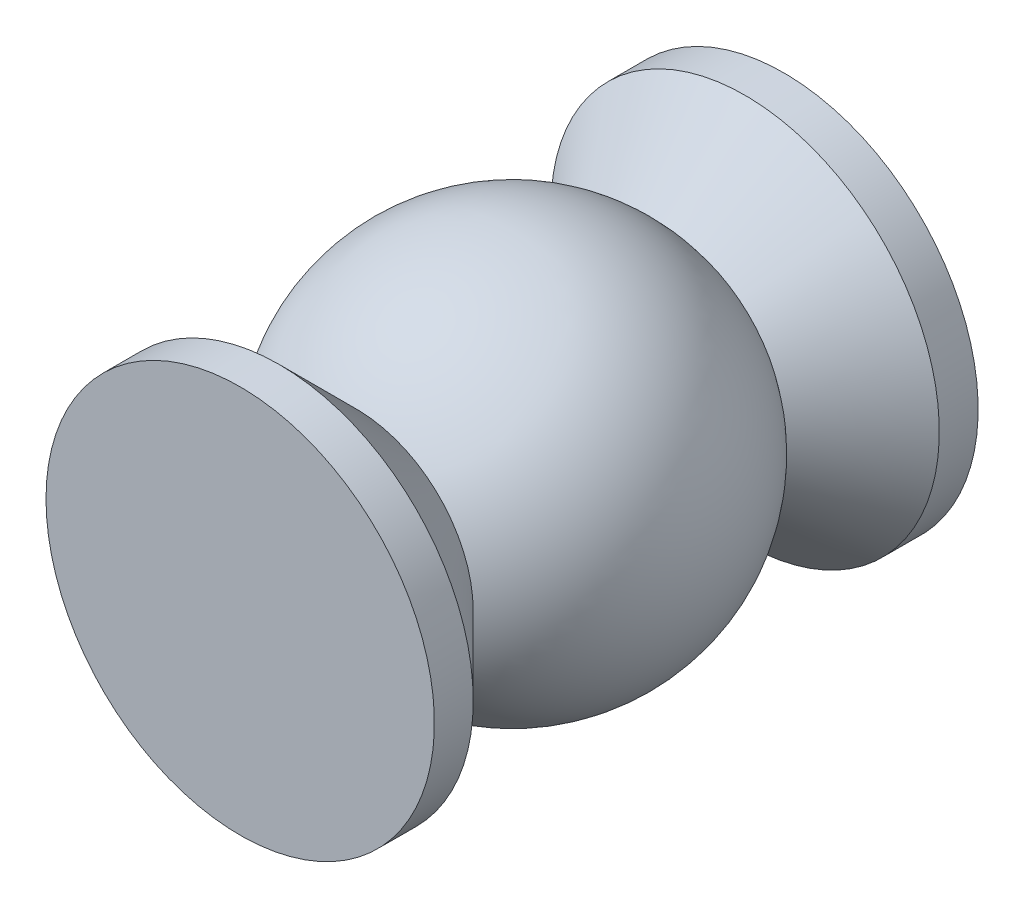
SolidWorks part; units mm, degrees
ref_plane "前视基准面" through (0, 0, 0) normal (0, 0, 1) x (1, 0, 0)
ref_plane "上视基准面" through (0, 0, 0) normal (0, 1, 0) x (1, 0, 0)
ref_plane "右视基准面" through (0, 0, 0) normal (1, 0, 0) x (0, 0, -1)
other "Configuration Table"
sketch "草图2" plane through (0, 0, 0) normal (0, 1, 0) x (1, 0, 0)
  line L0 (0, 0) -> (0, 57.4306) construction
  line L1 (0, 0) -> (59.0278, 0) construction
  line L2 (0, 35) -> (25, 35)
  line L3 (25, 35) -> (25, 30)
  line L4 (25, 30) -> (15, 20)
  line L5 (25, -30) -> (15, -20)
  line L6 (25, -35) -> (25, -30)
  line L7 (0, -35) -> (25, -35)
  line L8 (0, 35) -> (0, -35)
  arc A0 (15, 20) -> (15, -20) centre (0, 0) cw
  dimension "D1" = 25
  dimension "D2" = 5
  dimension "D3" = 35
  dimension "D4" = 20
  dimension "D5" = 135
revolve "旋转1" add sketch "草图2" angle 360 about L8
